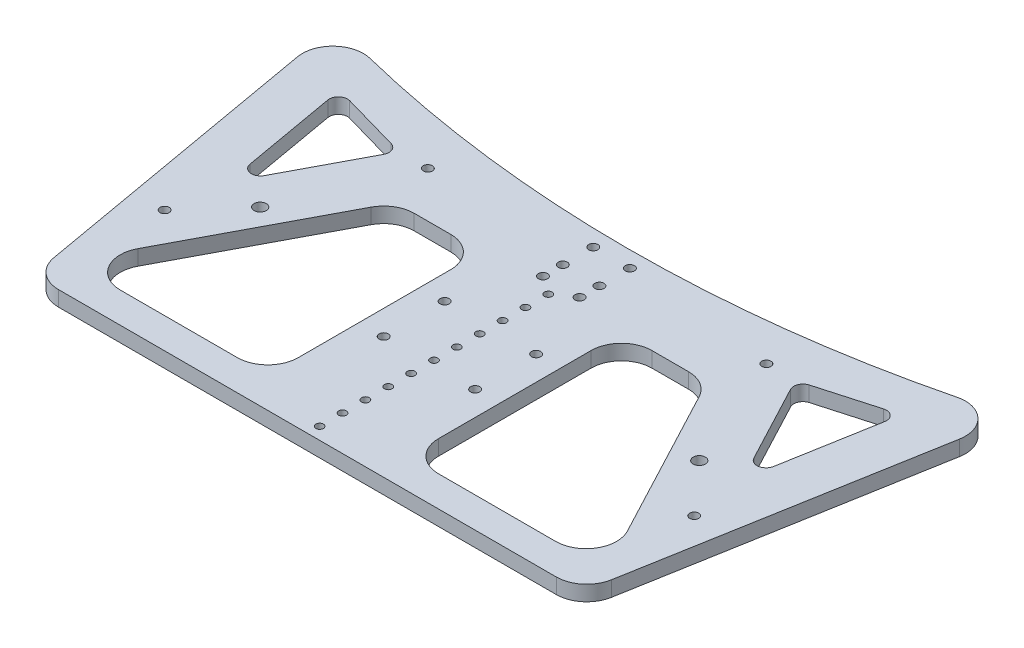
SolidWorks part; units mm, degrees
material "Thornel Mat VMA"
ref_plane "前视基准面" through (0, 0, 0) normal (0, 0, 1) x (1, 0, 0)
ref_plane "上视基准面" through (0, 0, 0) normal (0, 1, 0) x (1, 0, 0)
ref_plane "右视基准面" through (0, 0, 0) normal (1, 0, 0) x (0, 0, -1)
sketch "草图1" plane through (0, 0, 0) normal (0, 1, 0) x (1, 0, 0)
  line L0 (0, 130) -> (0, -202.379) construction
  line L1 (-90, 65) -> (90, 65)
  line L2 (-90, 65) -> (-90, -65)
  line L3 (-90, -65) -> (90, -65)
  line L4 (90, 65) -> (90, -65)
  line L5 (-90, 65) -> (90, -65) construction
  line L6 (-90, -65) -> (90, 65) construction
  line L17 (90, -65) -> (111.2997, 55.7964)
  line L18 (-90, -65) -> (-111.2997, 55.7964)
  circle A7 centre (0, 440) radius 400
  circle A8 centre (-72, -8.5) radius 2
  circle A9 centre (72, -8.5) radius 2
  point P0 (0, 0)
  dimension "D7" = 4
  dimension "D9" = 72
  dimension "D10" = 800
  dimension "D12" = 10
  dimension "D1" = 130
  dimension "D2" = 180
  dimension "D8" = 8.5
  dimension "D11" = 440
extrude "凸台-拉伸1" add sketch "草图1" along normal blind 5
sketch "草图2" plane through (0, 0, 0) normal (0, -1, 0) x (-1, 0, 0)
  line L1 (6, 18.25) -> (-6, 18.25) construction
  line L2 (6, 18.25) -> (6, 24.75) construction
  line L3 (6, 24.75) -> (-6, 24.75) construction
  line L4 (-6, 18.25) -> (-6, 24.75) construction
  line L5 (6, 18.25) -> (-6, 24.75) construction
  line L6 (6, 24.75) -> (-6, 18.25) construction
  circle A0 centre (6, 18.25) radius 1.5
  circle A1 centre (-6, 18.25) radius 1.5
  circle A2 centre (6, 24.75) radius 1.5
  circle A3 centre (-6, 24.75) radius 1.5
  circle A4 centre (-6, 34.75) radius 1.5
  circle A5 centre (6, 34.75) radius 1.5
  point P0 (0, 21.5)
  dimension "D4" = 3
  dimension "D5" = 3
  dimension "D6" = 3
  dimension "D7" = 3
  dimension "D8" = 3
  dimension "D9" = 3
  dimension "D1" = 6.5
  dimension "D2" = 12
  dimension "D3" = 21.5
  dimension "D10" = 10
  dimension "D11" = 10
extrude "切除-拉伸1" cut sketch "草图2" against normal through all
sketch "草图3" plane through (0, 5, 0) normal (0, 1, 0) x (1, 0, 0)
  line L0 (-90, -65) -> (90, -65) construction
  line L1 (35, 8.5) -> (45, 8.5)
  line L2 (35, 8.5) -> (35, -46.5)
  line L3 (35, -46.5) -> (45, -46.5)
  line L4 (45, 8.5) -> (45, -46.5)
  line L5 (35, 8.5) -> (45, -46.5) construction
  line L6 (35, -46.5) -> (45, 8.5) construction
  line L7 (0, 109.6967) -> (0, -116.804) construction
  line L8 (-35, -46.5) -> (-45, -46.5)
  line L9 (-45, 8.5) -> (-45, -46.5)
  line L10 (-35, 8.5) -> (-45, 8.5)
  line L11 (-35, 8.5) -> (-35, -46.5)
  circle A0 centre (40, -46.5) radius 5
  circle A1 centre (40, 8.5) radius 5
  circle A2 centre (-40, -46.5) radius 5
  circle A3 centre (-40, 8.5) radius 5
  point P0 (40, -19)
  dimension "D1" = 55
  dimension "D2" = 10
  dimension "D3" = 40
  dimension "D4" = 18.5
extrude "切除-拉伸2" cut sketch "草图3" against normal blind 3 contours L11 A3 L9 A2 | A3 L10 | A3 L10 | A2 L8 | A1 L2 A0 L4 | L3 A0 | L3 A0 | L1 A1 | L1 A1
sketch "草图4" plane through (0, 5, 0) normal (0, 1, 0) x (1, 0, 0)
  line L0 (72, -41.5) -> (72, -51.5)
  line L1 (72, -8.5) -> (31.5932, 6.2069)
  circle A0 centre (72, -8.5) radius 33
  circle A1 centre (72, -8.5) radius 43
  line M6 (45, 8.5) -> (45, -46.5)
  line M8 (35, -46.5) -> (35, 8.5)
  dimension "D1" = 66
  dimension "D2" = 86
  dimension "D3" = 110
extrude "切除-拉伸3" cut sketch "草图4" against normal blind 3 contours A1 A0 L1 M8 M6 | L1 A1 M8 | A1 L0 A0 M6
sketch "草图5" plane through (0, 5, 0) normal (0, 1, 0) x (1, 0, 0)
  line L0 (23, 15) -> (23, -55)
  line L1 (23, -55) -> (88, -55)
  line L2 (88, -55) -> (51, 15)
  line L3 (51, 15) -> (23, 15)
  line L4 (0, 95.0959) -> (0, -117.8936) construction
  line L5 (-88, -55) -> (-51, 15)
  line L6 (-23, -55) -> (-88, -55)
  line L7 (-23, 15) -> (-23, -55)
  line L8 (-51, 15) -> (-23, 15)
  dimension "D1" = 70
  dimension "D2" = 65
  dimension "D3" = 15
  dimension "D4" = 28
  dimension "D5" = 23
extrude "切除-拉伸4" cut sketch "草图5" against normal through all
fillet "圆角1" radius 10 8 edges at (-23, 2.5, 55) (-88, 2.5, 55) (88, 2.5, 55) (23, 2.5, 55) (23, 2.5, -15) (51, 2.5, -15) (-51, 2.5, -15) (-23, 2.5, -15)
fillet "圆角2" radius 10 2 edges at (90, 2.5, 65) (-90, 2.5, 65)
fillet "圆角3" radius 10 2 edges at (111.2997, 2.5, -55.7964) (-111.2997, 2.5, -55.7964)
sketch "草图7" plane through (0, 5, 0) normal (0, 1, 0) x (1, 0, 0)
  line L0 (-65, 30) -> (-84.3459, -6.6003)
  line L1 (-84.3459, -6.6003) -> (-92.16, 37.7161)
  line L2 (-92.16, 37.7161) -> (-65, 30)
  line L3 (-53.8157, 9.6731) -> (-80.2442, -40.3269) construction
  line L4 (-91.4571, -56.7365) -> (-108.572, 40.3268) construction
  line L5 (0, 179.2069) -> (0, -134.9737) construction
  line L6 (84.3459, -6.6003) -> (92.16, 37.7161)
  line L7 (65, 30) -> (84.3459, -6.6003)
  line L8 (92.16, 37.7161) -> (65, 30)
  dimension "D1" = 78
  dimension "D2" = 65
  dimension "D3" = 30
  dimension "D4" = 45
extrude "切除-拉伸6" cut sketch "草图7" against normal through all
fillet "圆角4" radius 3 6 edges at (84.3459, 2.5, 6.6003) (65, 2.5, -30) (-84.3459, 2.5, 6.6003) (-92.16, 2.5, -37.7161) (-65, 2.5, -30) (92.16, 2.5, -37.7161)
sketch "草图8" plane through (0, 0, 0) normal (0, -1, 0) x (-1, 0, 0)
  circle A0 centre (-55.5135, 30) radius 1.5
  circle A1 centre (-86.8472, -25) radius 1.5
  circle A2 centre (55.5135, 30) radius 1.5
  circle A3 centre (86.8472, -25) radius 1.5
  dimension "D1" = 3
  dimension "D2" = 3
  dimension "D3" = 3
  dimension "D4" = 3
extrude "切除-拉伸7" cut sketch "草图8" against normal through all
sketch "草图9" plane through (0, 0, 0) normal (0, -1, 0) x (1, 0, 0)
  circle A0 centre (0, -14) radius 1.25
  circle A1 centre (0, -6.5) radius 1.25
  circle A2 centre (0, 1) radius 1.25
  circle A3 centre (0, 8.5) radius 1.25
  circle A4 centre (0, 16) radius 1.25
  circle A5 centre (0, 23.5) radius 1.25
  circle A6 centre (0, 31) radius 1.25
  circle A7 centre (0, 38.5) radius 1.25
  circle A8 centre (0, 46) radius 1.25
  circle A9 centre (0, 53.5) radius 1.25
  circle A10 centre (0, 61) radius 1.25
  dimension "D1" = 2.5
  dimension "D2" = 14
  dimension "D4" = 7.5
  dimension "D3" = 11
extrude "切除-拉伸8" cut sketch "草图9" against normal through all
sketch "草图10" plane through (0, 0, 0) normal (0, -1, 0) x (1, 0, 0)
  line L0 (0, 65) -> (0, -40) construction
  line L1 (-81.609, 65) -> (81.609, 65) construction
  line L3 (-15, 5) -> (15, 5) construction
  line L4 (-15, 5) -> (-15, 25) construction
  line L5 (-15, 25) -> (15, 25) construction
  line L6 (15, 5) -> (15, 25) construction
  line L7 (-15, 5) -> (15, 25) construction
  line L8 (-15, 25) -> (15, 5) construction
  arc A0 (96.316, -51.7691) -> (-96.316, -51.7691) centre (0, -440) ccw construction
  circle A1 centre (-15, 25) radius 1.5
  circle A2 centre (-15, 5) radius 1.5
  circle A3 centre (15, 5) radius 1.5
  circle A4 centre (15, 25) radius 1.5
  point P7 (0, 15)
  dimension "D4" = 3
  dimension "D5" = 3
  dimension "D1" = 30
  dimension "D2" = 40
  dimension "D3" = 20
extrude "切除-拉伸9" cut sketch "草图10" against normal through all
